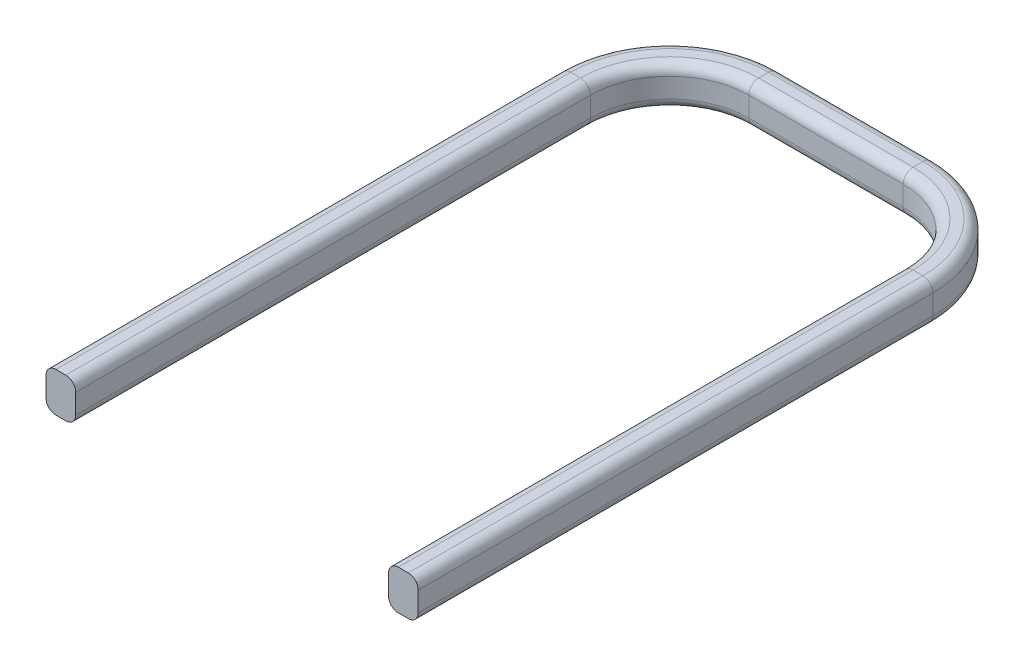
SolidWorks part; units mm, degrees
ref_plane "Front Plane" through (0, 0, 0) normal (0, 0, 1) x (1, 0, 0)
ref_plane "Top Plane" through (0, 0, 0) normal (0, 1, 0) x (1, 0, 0)
ref_plane "Right Plane" through (0, 0, 0) normal (1, 0, 0) x (0, 0, -1)
sketch "Sketch1" plane through (0, 0, 0) normal (0, 1, 0) x (1, 0, 0)
  line L0 (-3.95, 0) -> (-3.95, 13)
  line L1 (-1.95, 15) -> (1.95, 15)
  line L2 (3.95, 13) -> (3.95, 0)
  arc A0 (1.95, 15) -> (3.95, 13) centre (1.95, 13) cw
  arc A1 (-3.95, 13) -> (-1.95, 15) centre (-1.95, 13) cw
  point P2 (0, 15)
  point P10 (-3.95, 15)
  dimension "D3" = 2
  dimension "D1" = 15
  dimension "D2" = 3.95
sketch "Sketch2" plane through (0, 0, 0) normal (0, 0, 1) x (1, 0, 0)
  line L1 (-3.95, 0) -> (-4.7, 0)
  line L2 (-3.95, 0) -> (-3.95, 1)
  line L3 (-3.95, 1) -> (-4.7, 1)
  line L4 (-4.7, 0) -> (-4.7, 1)
  dimension "D1" = 1
  dimension "D2" = 0.75
sweep "Sweep1" add profiles "Sketch2" path "Sketch1"
fillet "Fillet1" radius 0.25 20 edges at (3.95, 0, -6.5) (3.3642, 0, -14.4142) (0, 0, -15) (-3.3642, 0, -14.4142) (4.7, 0, -6.5) (3.8945, 0, -14.9445) (0, 0, -15.75) (-3.8945, 0, -14.9445) (3.95, 1, -6.5) (3.3642, 1, -14.4142) (0, 1, -15) (-3.3642, 1, -14.4142) (4.7, 1, -6.5) (3.8945, 1, -14.9445) (0, 1, -15.75) (-3.8945, 1, -14.9445) (-3.95, 0, -6.5) (-4.7, 0, -6.5) (-3.95, 1, -6.5) (-4.7, 1, -6.5)
